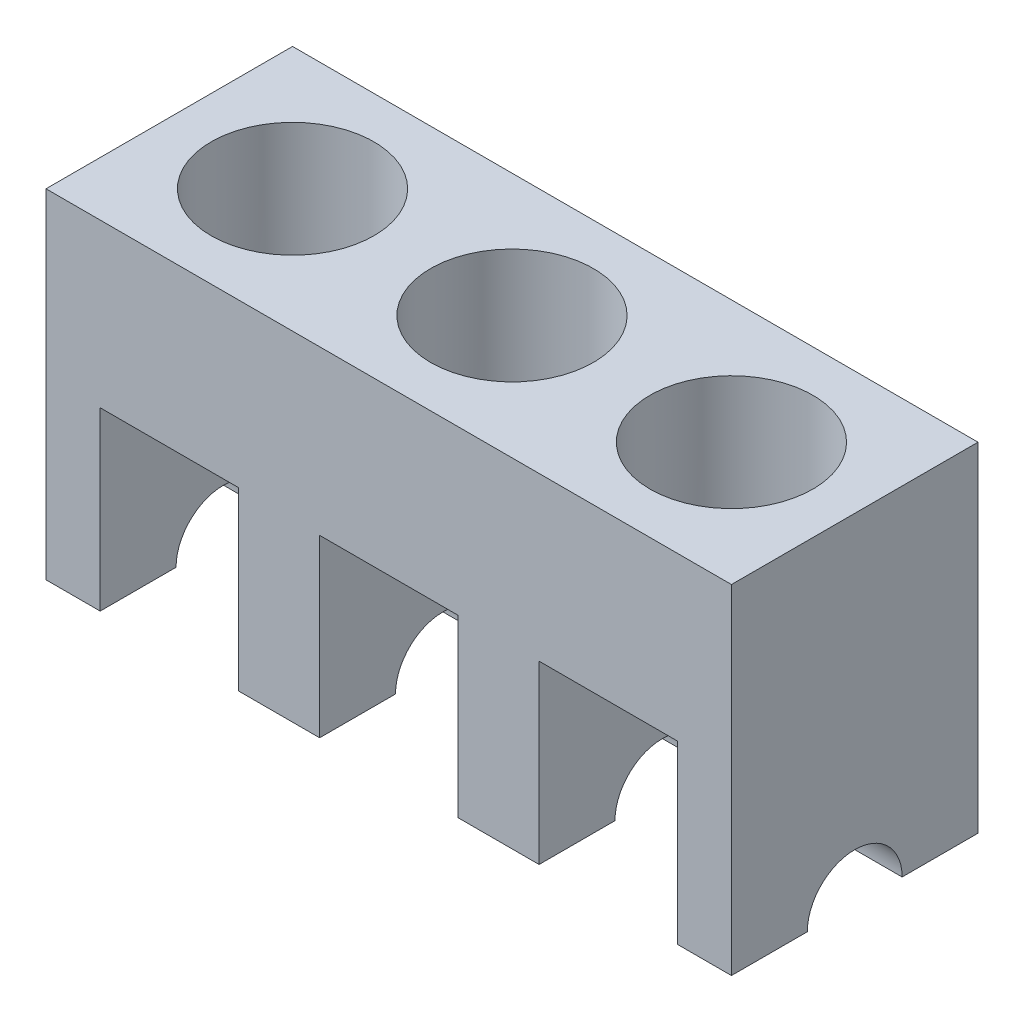
SolidWorks part; units mm, degrees
ref_plane "Front Plane" through (0, 0, 0) normal (0, 0, 1) x (1, 0, 0)
ref_plane "Top Plane" through (0, 0, 0) normal (0, 1, 0) x (1, 0, 0)
ref_plane "Right Plane" through (0, 0, 0) normal (1, 0, 0) x (0, 0, -1)
sketch "Sketch1" plane through (0, 0, 0) normal (0, 1, 0) x (1, 0, 0)
  line L0 (-56.7788, 2284.415) -> (-56.7788, -26.985)
  line L1 (-56.7788, -26.985) -> (6369.4212, -26.985)
  line L2 (6369.4212, -26.985) -> (6369.4212, 2284.415)
  line L3 (6369.4212, 2284.415) -> (-56.7788, 2284.415)
  dimension "D1" = 6426.2
  dimension "D2" = 2311.4
extrude "Boss-Extrude1" add sketch "Sketch1" along normal blind 3175
sketch "Sketch2" plane through (0, 3175, 0) normal (0, 1, 0) x (1, 0, 0)
  line L0 (-56.7788, 2284.415) -> (-56.7788, -26.985) construction
  line L1 (6369.4212, 2284.415) -> (-56.7788, 2284.415) construction
  line L3 (1098.9212, 1128.715) -> (8216.5621, 1128.715) construction
  line L4 (-56.7788, -26.985) -> (6369.4212, -26.985) construction
  circle A0 centre (1098.9212, 1128.715) radius 763.27
  circle A1 centre (3156.3212, 1128.715) radius 763.27
  circle A2 centre (5213.7212, 1128.715) radius 763.27
  dimension "D1" = 1155.7
  dimension "D3" = 1526.54
  dimension "D2" = 1155.7
  dimension "D4" = 1155.7
  dimension "D5" = 2057.4
  dimension "D6" = 1155.7
  dimension "D7" = 2057.4
extrude "Cut-Extrude1" cut sketch "Sketch2" against normal offset from surface (2057.4 mm away) 2057.4 up to face at (3156.3212, 3175, -1128.715)
sketch "Sketch6" plane through (0, 0, 0) normal (0, 0, 1) x (1, 0, 0)
  line L5 (2508.6212, -7.1583) -> (3804.0212, -7.1583)
  line L6 (2508.6212, -7.1583) -> (2508.6212, 1643.8417)
  line L7 (2508.6212, 1643.8417) -> (3804.0212, 1643.8417)
  line L8 (3804.0212, -7.1583) -> (3804.0212, 1643.8417)
  line L9 (4566.0212, 0) -> (5861.4212, 0)
  line L10 (4566.0212, 0) -> (4566.0212, 1651)
  line L11 (4566.0212, 1651) -> (5861.4212, 1651)
  line L12 (5861.4212, 0) -> (5861.4212, 1651)
  line L13 (6369.4212, 3175) -> (6369.4212, 0) construction
  line L18 (451.2212, 0) -> (1746.6212, 0)
  line L19 (451.2212, 0) -> (451.2212, 1651)
  line L20 (451.2212, 1651) -> (1746.6212, 1651)
  line L21 (1746.6212, 0) -> (1746.6212, 1651)
  line L22 (-56.7788, 3175) -> (-56.7788, 0) construction
  line L23 (-56.7788, 0) -> (6369.4212, 0) construction
  dimension "D1" = 508
  dimension "D2" = 1651
  dimension "D3" = 0
  dimension "D4" = 762
  dimension "D5" = 508
  dimension "D6" = 0
  dimension "D7" = 1651
extrude "Cut-Extrude3" cut sketch "Sketch6" against normal through all both and the other way through all
sketch "Sketch7" plane through (6369.4212, 0, 0) normal (1, 0, 0) x (0, 0, -1)
  line L0 (1128.715, 3175) -> (1128.715, -635.9583) construction
  line L1 (-26.985, 3175) -> (2284.415, 3175) construction
  line L2 (-26.985, 0) -> (2284.415, 0) construction
  circle A0 centre (1128.715, 0) radius 444.5
extrude "Cut-Extrude4" cut sketch "Sketch7" against normal through all both and the other way through all
